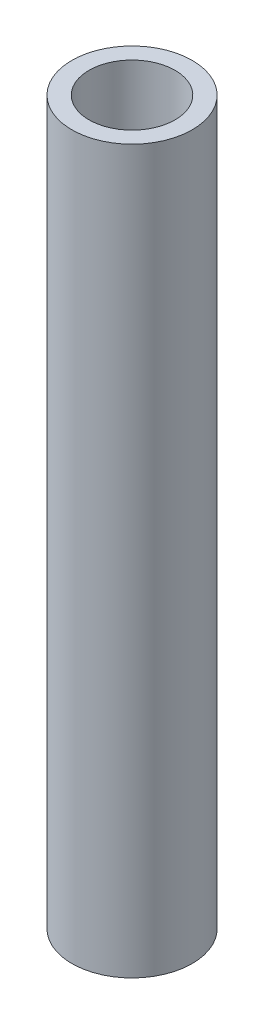
SolidWorks part; units mm, degrees
ref_plane "Front Plane" through (0, 0, 0) normal (0, 0, 1) x (1, 0, 0)
ref_plane "Top Plane" through (0, 0, 0) normal (0, 1, 0) x (1, 0, 0)
ref_plane "Right Plane" through (0, 0, 0) normal (1, 0, 0) x (0, 0, -1)
sketch "Sketch1" plane through (0, 0, 0) normal (0, 1, 0) x (1, 0, 0)
  circle A0 centre (0, 0) radius 2.5
  circle A1 centre (0, 0) radius 3.5
  dimension "D1" = 5
  dimension "D2" = 7
  dimension "D3" = 7
extrude "Boss-Extrude1" add sketch "Sketch1" along normal blind 42
